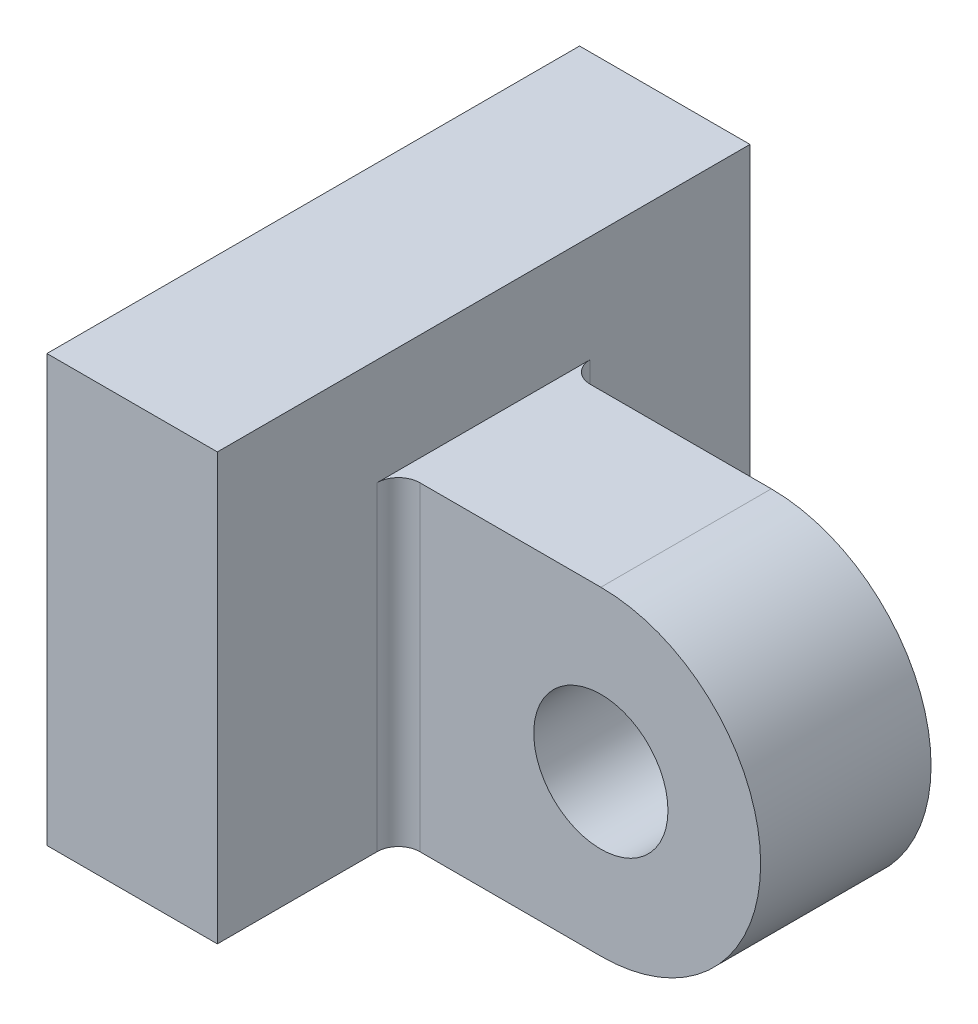
SolidWorks part; units mm, degrees
ref_plane "Front Plane" through (0, 0, 0) normal (0, 0, 1) x (1, 0, 0)
ref_plane "Top Plane" through (0, 0, 0) normal (0, 1, 0) x (1, 0, 0)
ref_plane "Right Plane" through (0, 0, 0) normal (1, 0, 0) x (0, 0, -1)
sketch "Sketch2" plane through (0, 0, 0) normal (0, 0, 1) x (1, 0, 0)
  line L4 (22.9129, 6.876) -> (22.9129, -27.6515) construction
  line L5 (22.9129, -2.8877) -> (5.4129, -2.8877)
  line L6 (22.9129, -17.8877) -> (5.4129, -17.8877)
  line L7 (5.4129, -2.8877) -> (5.4129, -17.8877)
  circle A0 centre (22.9129, -10.3877) radius 3.15
  arc A2 (22.9129, -17.8877) -> (22.9129, -2.8877) centre (22.9129, -10.3877) ccw
  dimension "D3" = 6.3
  dimension "D4" = 17.5
  dimension "D1" = 15
  dimension "D2" = 17.5
extrude "Boss-Extrude1" add sketch "Sketch2" along normal blind 8
sketch "Sketch3" plane through (5.4129, 0, 0) normal (-1, 0, 0) x (0, 0, 1)
  line L0 (8, -17.8877) -> (0, -17.8877) construction
  line L1 (-8.5, 2.1123) -> (16.5, 2.1123)
  line L2 (-8.5, 2.1123) -> (-8.5, -17.8877)
  line L3 (-8.5, -17.8877) -> (16.5, -17.8877)
  line L4 (16.5, 2.1123) -> (16.5, -17.8877)
  point P4 (4, -17.8877)
  point P7 (4, -17.8877)
  dimension "D1" = 25
  dimension "D2" = 20
extrude "Boss-Extrude2" add sketch "Sketch3" against normal blind 8
fillet "Fillet1" radius 1 2 edges at (13.4129, -10.3877, 0) (13.4129, -10.3877, 8)
